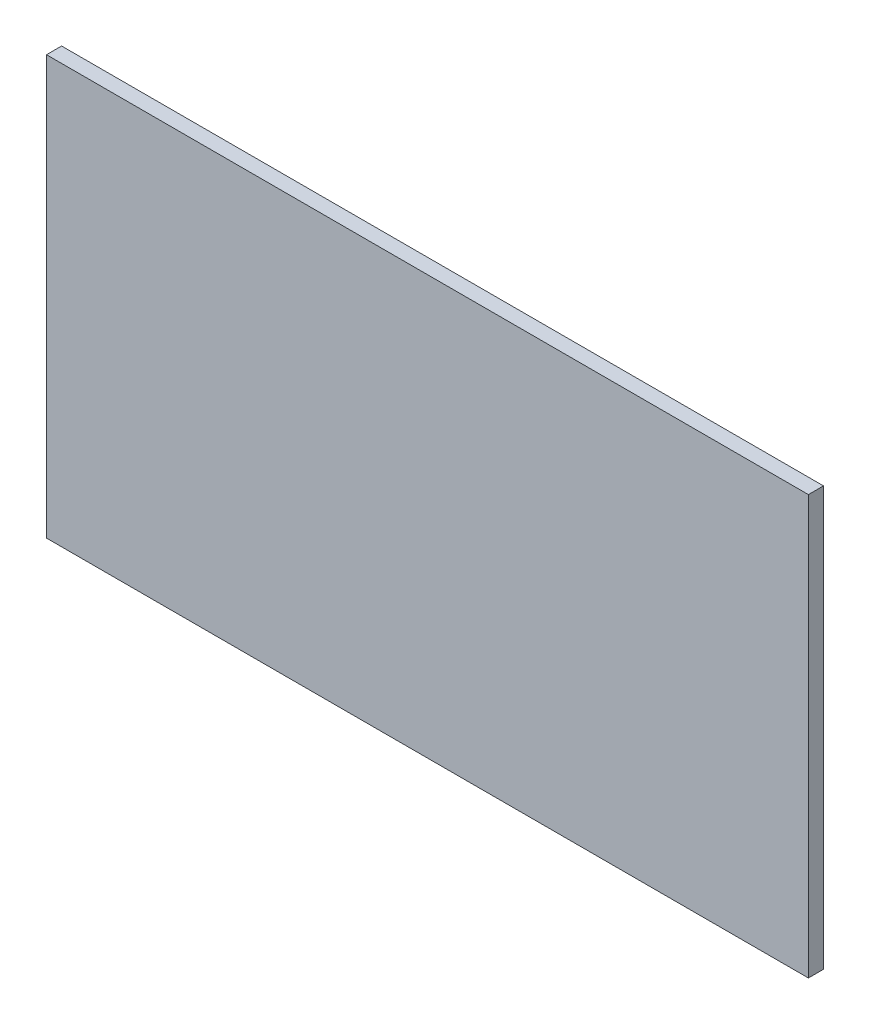
SolidWorks part; units mm, degrees
material "Faia"
ref_plane "Plano frontal" through (0, 0, 0) normal (0, 0, 1) x (1, 0, 0)
ref_plane "Plano superior" through (0, 0, 0) normal (0, 1, 0) x (1, 0, 0)
ref_plane "Plano direito" through (0, 0, 0) normal (1, 0, 0) x (0, 0, -1)
sketch "Esboço1" plane through (0, 0, 0) normal (0, 0, 1) x (1, 0, 0)
  line L1 (0, 0) -> (20.2, 0)
  line L2 (0, 0) -> (0, 11.1)
  line L3 (0, 11.1) -> (20.2, 11.1)
  line L4 (20.2, 0) -> (20.2, 11.1)
  dimension "D1" = 20.2
  dimension "D2" = 11.1
extrude "Ressalto-extrusão1" add sketch "Esboço1" along normal blind 0.4
